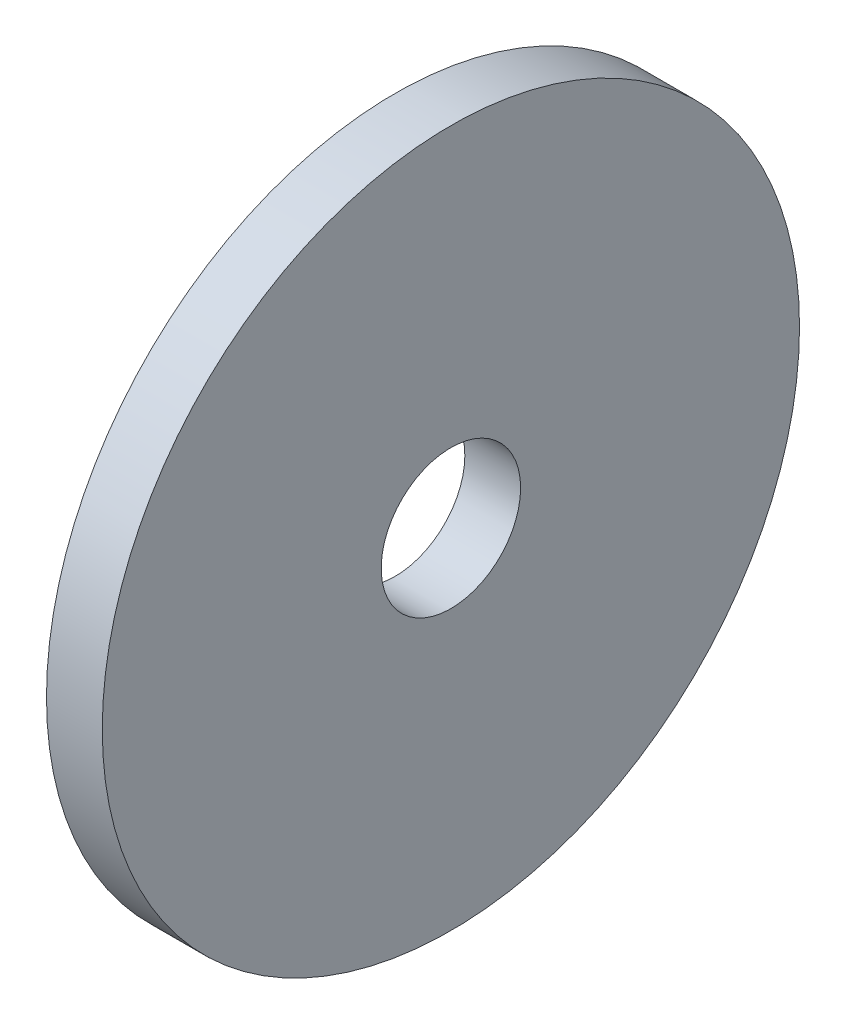
SolidWorks part; units mm, degrees
ref_plane "Front Plane" through (0, 0, 0) normal (1, 0, 0) x (0, 1, 0)
ref_plane "Top Plane" through (0, 0, 0) normal (0, 0, 1) x (0, 1, 0)
ref_plane "Right Plane" through (0, 0, 0) normal (0, 1, 0) x (-1, 0, 0)
sketch "Sketch1" plane through (0, 0, 0) normal (1, 0, 0) x (0, 1, 0)
  circle A0 centre (0, 0) radius 15.875
  circle A1 centre (0, 0) radius 3.175
  dimension "D1" = 6.35
  dimension "D2" = 31.75
extrude "Boss-Extrude1" add sketch "Sketch1" along normal blind 2.54
